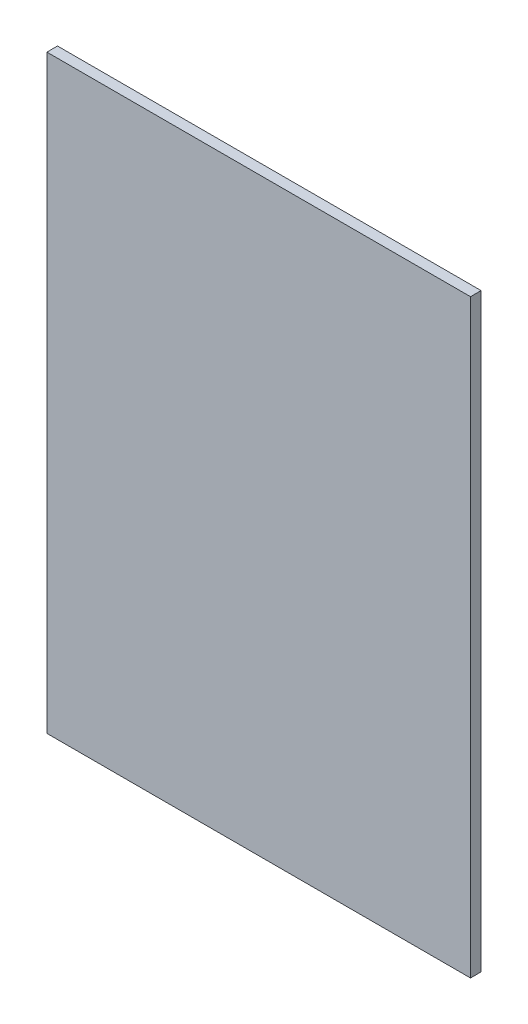
SolidWorks part; units mm, degrees
ref_plane "정면" through (0, 0, 0) normal (0, 0, 1) x (1, 0, 0)
ref_plane "윗면" through (0, 0, 0) normal (0, 1, 0) x (1, 0, 0)
ref_plane "우측면" through (0, 0, 0) normal (1, 0, 0) x (0, 0, -1)
sketch "스케치1" plane through (0, 0, 0) normal (0, 0, 1) x (1, 0, 0)
  line L1 (-2493.6139, -278.5708) -> (-2293.6139, -278.5708)
  line L2 (-2493.6139, -278.5708) -> (-2493.6139, 0)
  line L3 (-2493.6139, 0) -> (-2293.6139, 0)
  line L4 (-2293.6139, -278.5708) -> (-2293.6139, 0)
extrude "보스-돌출1" add sketch "스케치1" along normal blind 5
